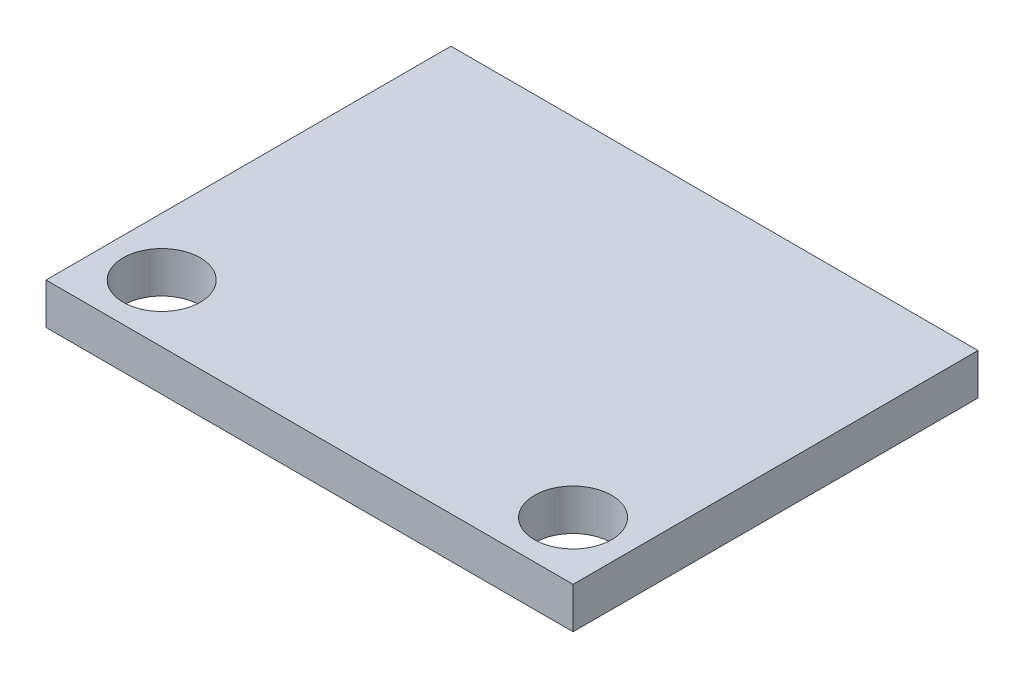
SolidWorks part; units mm, degrees
ref_plane "Front Plane" through (0, 0, 0) normal (0, 0, 1) x (1, 0, 0)
ref_plane "Top Plane" through (0, 0, 0) normal (0, 1, 0) x (1, 0, 0)
ref_plane "Right Plane" through (0, 0, 0) normal (1, 0, 0) x (0, 0, -1)
sketch "Sketch1" plane through (0, 0, 0) normal (0, 1, 0) x (1, 0, 0)
  line L0 (0, 7.875) -> (0, -7.875) construction
  line L1 (-10.25, -7.875) -> (10.25, -7.875)
  line L2 (-10.25, -7.875) -> (-10.25, 7.875)
  line L3 (-10.25, 7.875) -> (10.25, 7.875)
  line L4 (10.25, -7.875) -> (10.25, 7.875)
  line L5 (-10.25, -7.875) -> (10.25, 7.875) construction
  line L6 (-10.25, 7.875) -> (10.25, -7.875) construction
  circle A0 centre (8, -5.625) radius 1.5
  circle A1 centre (-8, -5.625) radius 1.5
  point P0 (0, 0)
  dimension "D5" = 3
  dimension "D1" = 15.75
  dimension "D2" = 20.5
  dimension "D3" = 2.25
  dimension "D4" = 2.25
extrude "Boss-Extrude1" add sketch "Sketch1" along normal blind 1.6
